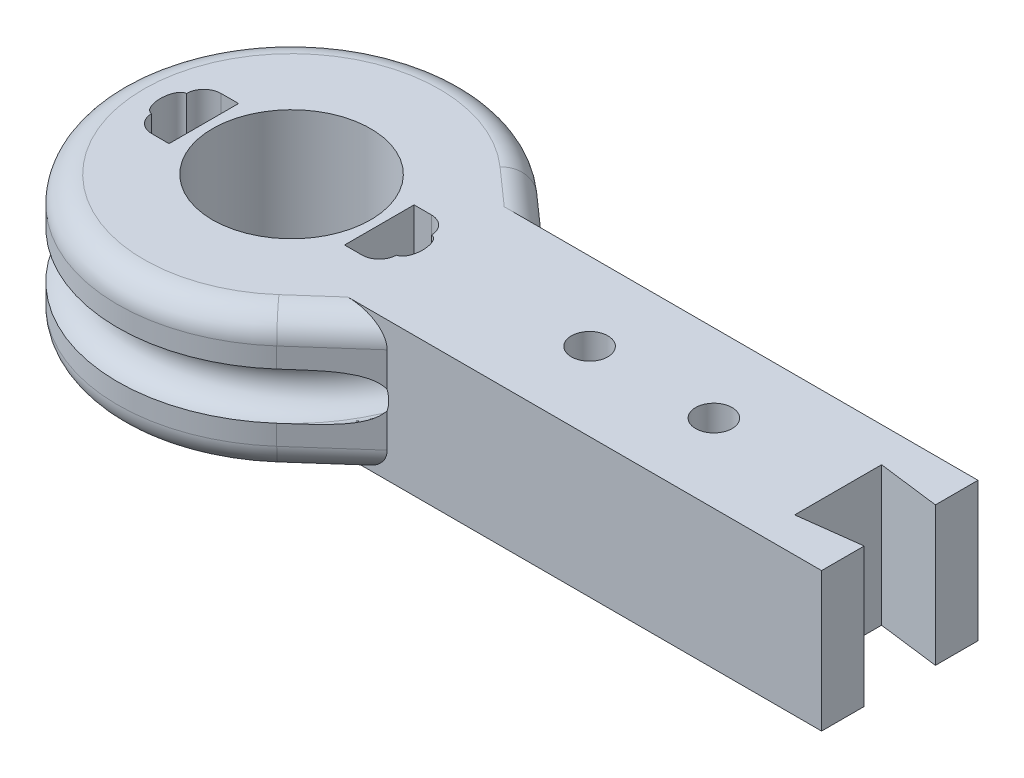
SolidWorks part; units mm, degrees
ref_plane "Front Plane" through (0, 0, 0) normal (0, 0, 1) x (1, 0, 0)
ref_plane "Top Plane" through (0, 0, 0) normal (0, 1, 0) x (1, 0, 0)
ref_plane "Right Plane" through (0, 0, 0) normal (1, 0, 0) x (0, 0, -1)
sketch "Sketch1" plane through (0, 0, 0) normal (0, 1, 0) x (1, 0, 0)
  line L0 (-12.4221, 0) -> (31.45, 0) construction
  line L1 (0, 8.1775) -> (0, -7.8417) construction
  line L2 (10, 4.5) -> (6.632, 7.4844)
  line L3 (10, -4.5) -> (35, -4.5)
  line L5 (10, 4.5) -> (35, 4.5)
  line L6 (35, -4.5) -> (35, -2.05)
  line L7 (10, -4.5) -> (35, 4.5) construction
  line L8 (10, 4.5) -> (35, -4.5) construction
  line L9 (10, -4.5) -> (6.632, -7.4844)
  line L10 (10, 4.5) -> (10, -4.5) construction
  line L11 (5.05, 2) -> (6.05, 2)
  line L12 (-5.05, -2) -> (-6.05, -2)
  line L13 (-5.05, -2) -> (-5.05, 2)
  line L14 (-5.05, 2) -> (-6.05, 2)
  line L18 (7.05, -1) -> (7.05, 0)
  line L19 (5.05, -2) -> (6.05, -2)
  line L20 (5.05, -2) -> (5.05, 2)
  line L21 (35, 2.05) -> (31.45, 2.5)
  line L23 (31.45, -2.5) -> (31.45, 2.5)
  line L26 (31.45, -2.5) -> (31.2787, -3.1603) construction
  line L27 (31.45, 2.5) -> (32.1221, 3.464) construction
  line L28 (35, -2.05) -> (31.45, -2.5)
  line L30 (35, 2.05) -> (35, 4.5)
  arc A0 (6.632, 7.4844) -> (6.632, -7.4844) centre (0, 0) ccw
  circle A1 centre (0, 0) radius 4.55
  arc A2 (-6.05, -2) -> (-7.05, -1) centre (-6.05, -1) cw
  arc A3 (-6.05, 2) -> (-7.05, 1) centre (-6.05, 1) ccw
  arc A6 (6.05, 2) -> (7.05, 1) centre (6.05, 1) cw
  arc A7 (6.05, -2) -> (7.05, -1) centre (6.05, -1) ccw
  ellipse E0 centre (-7.05, 0) end of major axis (-7.05, -1) minor radius 0.5 (-7.05, 1) -> (-7.05, -1) ccw
  ellipse E1 centre (7.05, 0) end of major axis (7.05, -1) minor radius 0.5 (7.05, -1) -> (7.05, 1) ccw
  point P7 (22.5, 0)
  point P12 (-6, 0)
  point P19 (-5.05, 0)
  point P20 (-4.55, 0)
  point P44 (35, 2.05)
  point P48 (35, -2.05)
  dimension "D1" = 20
  dimension "D4" = 9.1
  dimension "D8" = 1
  dimension "D9" = 3.55
  dimension "D2" = 25
  dimension "D3" = 9
  dimension "D5" = 4
  dimension "D6" = 2
  dimension "D7" = 0.5
  dimension "D10" = 2
  dimension "D11" = 1
  dimension "D13" = 1
  dimension "D14" = 2.45
extrude "Boss-Extrude2" add sketch "Sketch1" along normal blind 8
sketch "Sketch4" plane through (-6.6668, 16.5353, 0) normal (0, 0, 1) x (0, 1, 0)
  line L2 (-8.5353, -13.2988) -> (-8.5353, 3.3332) construction
  line L3 (-8.5353, 3.3332) -> (-16.5353, 3.3332) construction
  line L8 (-16.5353, -6.6668) -> (-4.9826, -6.6668) construction
  arc A1 (-13.8853, 3.3332) -> (-11.1853, 3.3332) centre (-12.5353, 3.3332) ccw
  ellipse E0 centre (-12.5353, 3.3332) end of major axis (-13.8853, 3.3332) minor radius 1.05 (-11.1853, 3.3332) -> (-13.8853, 3.3332) ccw
  point P0 (-12.5353, 3.3332)
  point P1 (-12.5353, 3.3332)
  point P13 (-8.5353, 3.3019)
  point P14 (0, 0)
  point P22 (-12.5353, 3.3332)
  dimension "D1" = 2.7
  dimension "D2" = 1.05
fillet "Fillet2" radius 1.5 6 edges at (8.316, 0, -5.9922) (8.316, 8, -5.9922) (8.316, 0, 5.9922) (8.316, 8, 5.9922) (-10, 0, 0) (-10, 8, 0)
sketch "Sketch5" plane through (0, 8, 0) normal (0, 1, 0) x (1, 0, 0)
  line L0 (10, 6.5426) -> (10, -6.3371) construction
  line L1 (31.45, 7.6045) -> (31.45, -7.4675) construction
  line L2 (0, 0) -> (39.1502, 0) construction
  circle A0 centre (17.15, 0) radius 1.05
  circle A1 centre (24.3, 0) radius 1.05
  point P0 (10, -4.5)
  point P1 (10, 4.5)
  point P16 (31.45, 0.0685)
  dimension "D2" = 2.1
  dimension "D1" = 7.15
  dimension "D3" = 7.15
extrude "Cut-Extrude1" cut sketch "Sketch5" against normal blind 10 contours A1 | A0
revolve "Cut-Revolve1" cut sketch "Sketch4" angle 360 about L8
